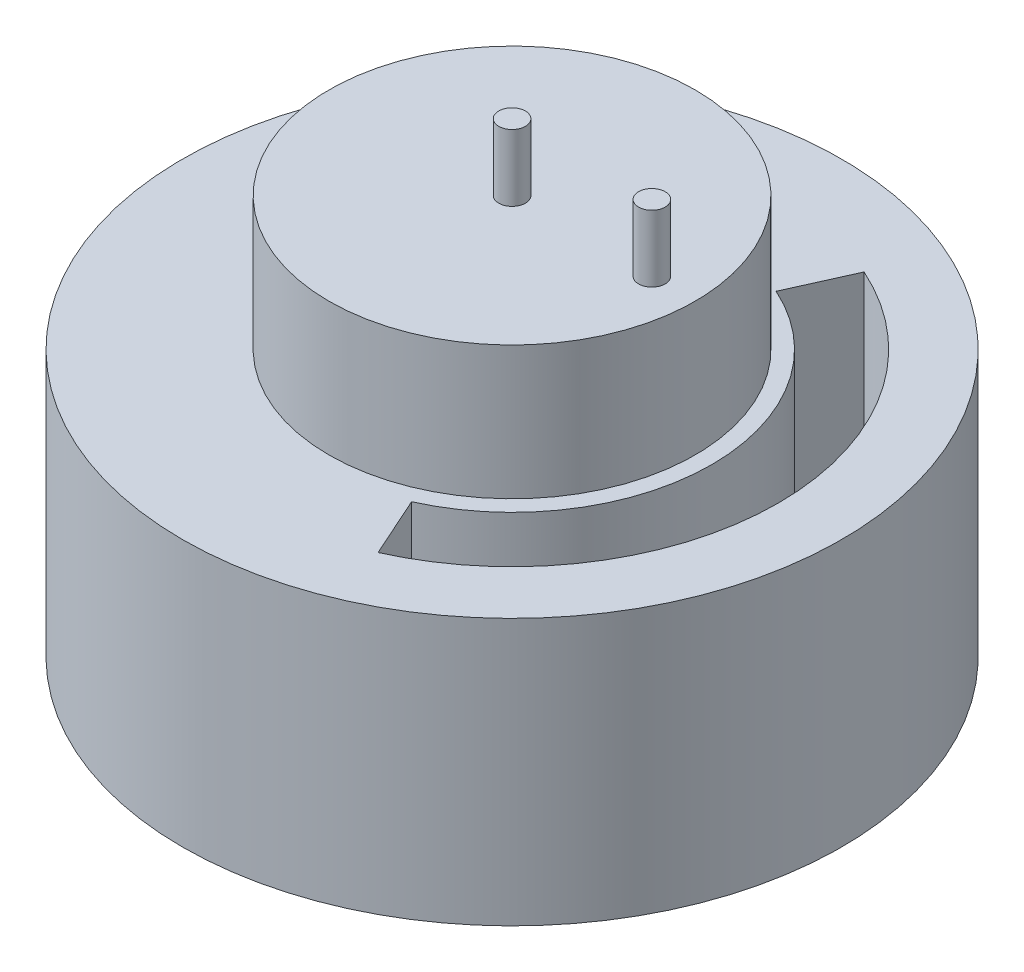
SolidWorks part; units mm, degrees
ref_plane "Plano frontal" through (0, 0, 0) normal (0, 0, 1) x (1, 0, 0)
ref_plane "Plano superior" through (0, 0, 0) normal (0, 1, 0) x (1, 0, 0)
ref_plane "Plano direito" through (0, 0, 0) normal (1, 0, 0) x (0, 0, -1)
sketch "Esboço1" plane through (0, 0, 0) normal (0, 1, 0) x (1, 0, 0)
  line L0 (0, 0) -> (-10, 0) construction
  line L1 (0, 0) -> (10, 0) construction
  line L2 (-10, 0) -> (-10, -17.3205) construction
  line L3 (10, 0) -> (10, -17.3205) construction
  line L4 (10, -27.2235) -> (-10, -27.2235) construction
  line L9 (-10, -22.9129) -> (-10, -27.2235) construction
  line L11 (10, -22.9129) -> (10, -27.2235) construction
  arc A1 (12.375, -21.4341) -> (-12.375, -21.4341) centre (0, 0) ccw
  circle A3 centre (0, 0) radius 24.75
extrude "Ressalto-extrusão2" add sketch "Esboço1" along normal blind 20
ref_plane "Plano1" through (0, 20, 0) normal (0, 1, 0) x (1, 0, 0)
sketch "Esboço3" plane through (0, 20, 0) normal (0, 1, 0) x (1, 0, 0)
  circle A0 centre (0, 0) radius 13.75
extrude "Boss-Extrude1" add sketch "Esboço3" along normal blind 10
sketch "Sketch1" plane through (0, 20, 0) normal (0, 1, 0) x (1, 0, 0)
  circle A0 centre (0, 0) radius 20
  circle A1 centre (0, 0) radius 25
ref_plane "Plane1" through (0, 30, 0) normal (0, 1, 0) x (1, 0, 0)
sketch "Sketch2" plane through (0, 30, 0) normal (0, 1, 0) x (1, 0, 0)
  line L0 (1, 0) -> (10.5, 0) construction
  circle A0 centre (0, 0) radius 1
  circle A1 centre (10.5, 0) radius 1
extrude "Boss-Extrude2" add sketch "Sketch2" along normal blind 5
ref_plane "Plane2" through (0, 20, 0) normal (0, 1, 0) x (1, 0, 0)
sketch "Sketch3" plane through (0, 20, 0) normal (0, 1, 0) x (1, 0, 0)
  line L0 (0, 0) -> (15, 0) construction
  line L1 (0, 0) -> (8.1857, -18.2481) construction
  line L2 (0, 0) -> (8.1857, 18.2481) construction
  line L3 (8.1857, -18.2481) -> (6.1393, -13.6861)
  line L4 (8.1857, 18.2481) -> (6.1393, 13.6861)
  arc A0 (6.1393, -13.6861) -> (6.1393, 13.6861) centre (0, 0) ccw
  arc A1 (8.1857, -18.2481) -> (8.1857, 18.2481) centre (0, 0) ccw
  dimension "D1" = 65.84
extrude "Cut-Extrude2" cut sketch "Sketch3" against normal up to surface (20 mm away) up to face at (0, 0, 24.75)
